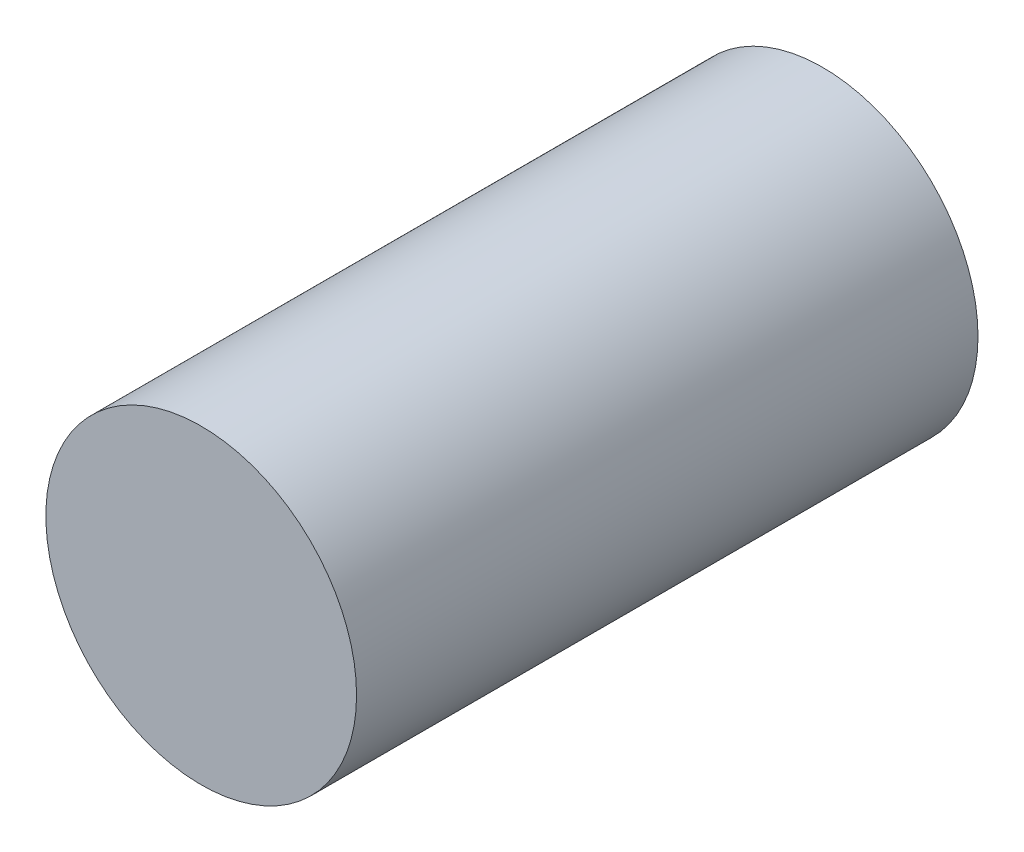
SolidWorks part; units mm, degrees
ref_plane "Piano frontale" through (0, 0, 0) normal (0, 0, 1) x (1, 0, 0)
ref_plane "Piano superiore" through (0, 0, 0) normal (0, 1, 0) x (1, 0, 0)
ref_plane "Piano destro" through (0, 0, 0) normal (1, 0, 0) x (0, 0, -1)
sketch "Schizzo1" plane through (0, 0, 0) normal (0, 0, 1) x (1, 0, 0)
  circle A0 centre (0, 0) radius 7.5
  dimension "D1" = 15
extrude "Estrusione-Estrusione1" add sketch "Schizzo1" along normal blind 30
